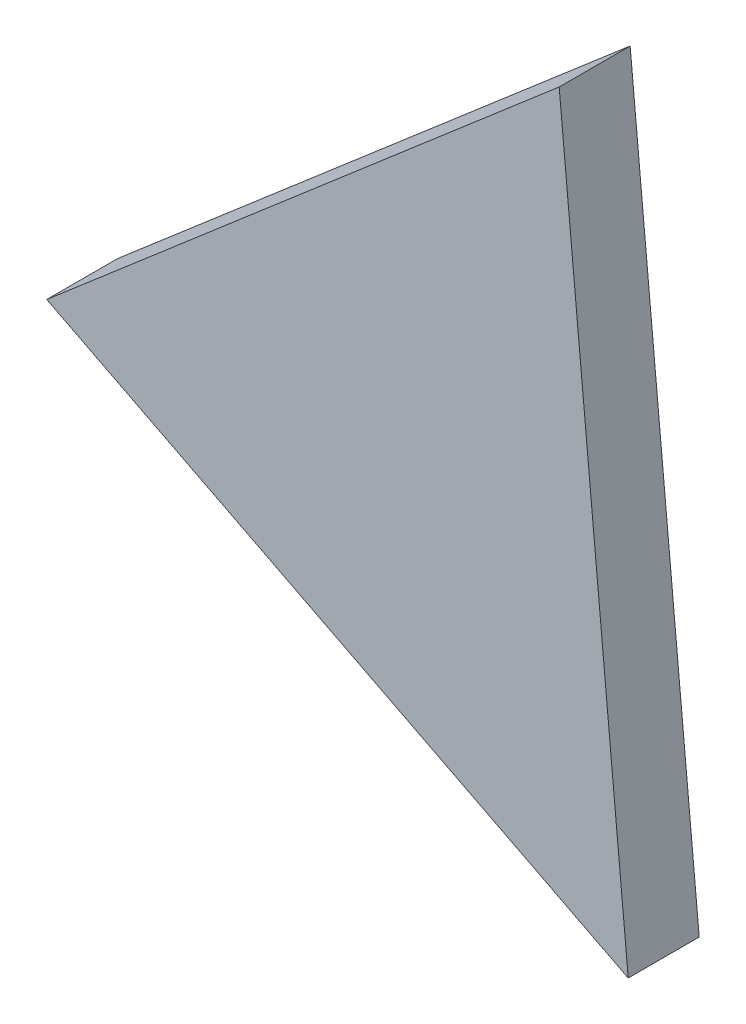
SolidWorks part; units mm, degrees
ref_plane "Front Plane" through (0, 0, 0) normal (0, 0, 1) x (1, 0, 0)
ref_plane "Top Plane" through (0, 0, 0) normal (0, 1, 0) x (1, 0, 0)
ref_plane "Right Plane" through (0, 0, 0) normal (1, 0, 0) x (0, 0, -1)
sketch "Sketch1" plane through (0, 0, 0) normal (0, 0, 1) x (1, 0, 0)
  line L0 (78.4197, -149.7713) -> (49.2295, 161.733)
  line L1 (49.2295, 161.733) -> (-167.304, -24.2996)
  line L2 (-167.304, -24.2996) -> (78.4197, -149.7713)
extrude "Boss-Extrude1" add sketch "Sketch1" against normal blind 30
equation "\"D1@Boss-Extrude1\"=\"wall_thick@4Vnaosei.Assembly\""
